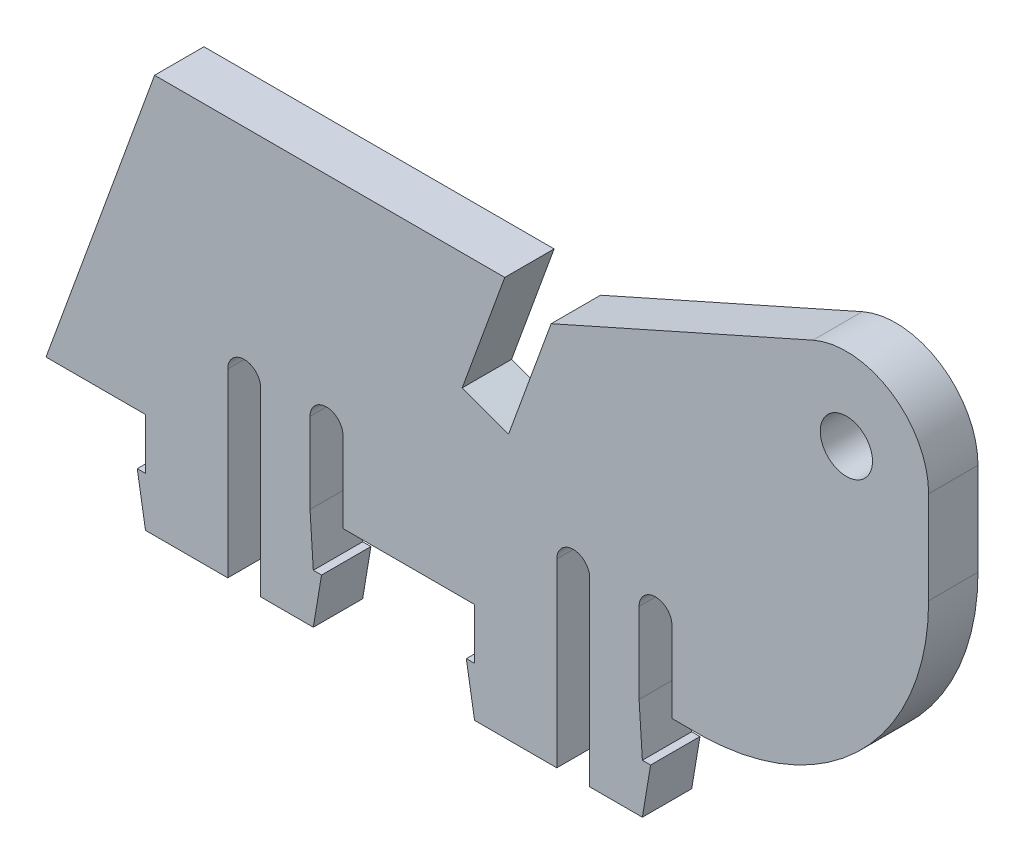
SolidWorks part; units mm, degrees
ref_plane "Front Plane" through (0, 0, 0) normal (0, 0, 1) x (1, 0, 0)
ref_plane "Top Plane" through (0, 0, 0) normal (0, 1, 0) x (1, 0, 0)
ref_plane "Right Plane" through (0, 0, 0) normal (1, 0, 0) x (0, 0, -1)
sketch "Sketch1" plane through (0, 0, 0) normal (0, 0, 1) x (1, 0, 0)
  line L0 (107.5, 145.7123) -> (-107.5, 145.7123) construction
  line L1 (-44.5347, 169.9086) -> (-60.4441, 162.8212)
  line L2 (-60.4441, 162.8212) -> (-63.0315, 155.7123)
  line L3 (-63.0315, 155.7123) -> (-65.8506, 156.7383)
  line L4 (-65.8506, 156.7383) -> (-63.2632, 163.8473)
  line L5 (-84.5467, 163.8473) -> (-91.1473, 145.7123)
  line L11 (-37.5, 165.3413) -> (-37.5, 159.7123)
  line L13 (-42.7842, 211.3413) -> (-67.7631, 142.7123) construction
  line L14 (-67.2603, 211.3413) -> (-92.2392, 142.7123) construction
  line L22 (-91.1473, 145.7123) -> (-51.5, 145.7123)
  line L24 (-63.0315, 155.7123) -> (-65.8506, 156.7383) construction
  line L25 (-47.0687, 208.3413) -> (-70.9557, 142.7123) construction
  line L26 (-63.2632, 163.8473) -> (-84.5467, 163.8473)
  circle A0 centre (-42.5, 165.3413) radius 1.5875
  arc A2 (-44.5347, 169.9086) -> (-37.5, 165.3413) centre (-42.5, 165.3413) cw
  arc A3 (-51.5, 145.7123) -> (-37.5, 159.7123) centre (-51.5, 159.7123) ccw
  dimension "D1" = 3.175
  dimension "D5" = 5
  dimension "D3" = 14
  dimension "D2" = 7.5652
extrude "Boss-Extrude1" add sketch "Sketch1" along normal up to vertex (3 mm away)
sketch "Sketch3" plane through (0, 0, 0) normal (0, 0, -1) x (-1, 0, 0)
  line B0 (54.9, 142.6123) -> (55.1, 145.7123)
  line B1 (53.1, 145.7123) -> (51.1, 145.7123)
  line B2 (65.1, 142.6123) -> (65.1, 145.7123)
  line B3 (65.1, 145.7123) -> (67.1, 145.7123)
  line B4 (58.1, 150.6123) -> (58.1, 139.6123)
  line B5 (65.1, 139.6123) -> (60.1, 139.6123)
  line B6 (60, 150.6123) -> (60, 134.8123) construction
  line B7 (55.1, 145.7123) -> (55.1, 150.6123)
  line B8 (53.1, 150.6123) -> (53.1, 145.7123)
  line B9 (54.9, 142.6123) -> (54.4, 142.6123)
  line B10 (54.4, 142.6123) -> (54.9, 139.6123)
  line B11 (58.1, 139.6123) -> (54.9, 139.6123)
  line B12 (60.1, 139.6123) -> (60.1, 150.6123)
  line B13 (65.1, 142.6123) -> (65.6, 142.6123)
  line B14 (65.6, 142.6123) -> (65.1, 139.6123)
  arc B15 (60.1, 150.6123) -> (58.1, 150.6123) centre (59.1, 150.6123) ccw
  arc B16 (55.1, 150.6123) -> (53.1, 150.6123) centre (54.1, 150.6123) ccw
  line B17 (67.1, 142.7123) -> (51.1, 142.7123) construction
  line B18 (67.1, 142.7123) -> (67.1, 145.7123) construction
  line B19 (59.1, 150.6123) -> (54.1, 150.6123) construction
  line B20 (51.1, 142.7123) -> (51.1, 145.7123) construction
  line B21 (65.1, 145.7123) -> (53.1, 145.7123) construction
  line B22 (67.1, 145.7123) -> (67.1, 152.7123)
  line B23 (67.1, 152.7123) -> (51.1, 152.7123)
  line B24 (51.1, 152.7123) -> (51.1, 145.7123)
  line B25 (74.9, 142.6123) -> (75.1, 145.7123)
  line B26 (73.1, 145.7123) -> (71.1, 145.7123)
  line B27 (85.1, 142.6123) -> (85.1, 145.7123)
  line B28 (85.1, 145.7123) -> (87.1, 145.7123)
  line B29 (78.1, 150.6123) -> (78.1, 139.6123)
  line B30 (85.1, 139.6123) -> (80.1, 139.6123)
  line B31 (80, 150.6123) -> (80, 134.8123) construction
  line B32 (75.1, 145.7123) -> (75.1, 150.6123)
  line B33 (73.1, 150.6123) -> (73.1, 145.7123)
  line B34 (74.9, 142.6123) -> (74.4, 142.6123)
  line B35 (74.4, 142.6123) -> (74.9, 139.6123)
  line B36 (78.1, 139.6123) -> (74.9, 139.6123)
  line B37 (80.1, 139.6123) -> (80.1, 150.6123)
  line B38 (85.1, 142.6123) -> (85.6, 142.6123)
  line B39 (85.6, 142.6123) -> (85.1, 139.6123)
  arc B40 (80.1, 150.6123) -> (78.1, 150.6123) centre (79.1, 150.6123) ccw
  arc B41 (75.1, 150.6123) -> (73.1, 150.6123) centre (74.1, 150.6123) ccw
  line B42 (87.1, 142.7123) -> (71.1, 142.7123) construction
  line B43 (79.1, 150.6123) -> (74.1, 150.6123) construction
  line B44 (71.1, 142.7123) -> (71.1, 145.7123) construction
  line B45 (85.1, 145.7123) -> (73.1, 145.7123) construction
  line B46 (87.1, 145.7123) -> (87.1, 152.7123)
  line B47 (87.1, 152.7123) -> (71.1, 152.7123)
  line B48 (71.1, 152.7123) -> (71.1, 145.7123)
sketch_block_instance "Block1-8"
sketch_block "Block1" parameters "D1"=1, "D2"=8, "D3"=3, "D4"=3.1, "D5"=10, "D6"=0.2, "D7"=0.5, "D8"=3, "D9"=4.3072, "D10"=5, "D11"=0.5
sketch_block_instance "Block1-10"
extrude "tabs" add sketch "Sketch3" against normal up to surface (3 mm away) up to face at (-59.5179, 158.8364, 3)
sketch "Sketch4" plane through (0, 0, 0) normal (0, 0, -1) x (-1, 0, 0)
  line L0 (55.1, 145.7123) -> (55.1, 150.6123) construction
  line L1 (75.1, 145.7123) -> (75.1, 150.6123) construction
  line L2 (55.1, 145.7123) -> (55.1, 150.6123)
  line L3 (75.1, 145.7123) -> (75.1, 150.6123)
  line L4 (53.1, 150.6123) -> (53.1, 145.7123)
  line L5 (53.1, 145.7123) -> (55.1, 145.7123)
  line L7 (58.1, 150.6123) -> (58.1, 145.7123)
  line L8 (58.1, 145.7123) -> (60.1, 145.7123)
  line L9 (60.1, 145.7123) -> (60.1, 150.6123)
  line L10 (73.1, 150.6123) -> (73.1, 145.7123)
  line L11 (73.1, 145.7123) -> (75.1, 145.7123)
  line L12 (78.1, 150.6123) -> (78.1, 145.7123)
  line L13 (78.1, 145.7123) -> (80.1, 145.7123)
  line L14 (80.1, 145.7123) -> (80.1, 150.6123)
  arc A0 (60.1, 150.6123) -> (58.1, 150.6123) centre (59.1, 150.6123) ccw construction
  arc A1 (55.1, 150.6123) -> (53.1, 150.6123) centre (54.1, 150.6123) ccw construction
  arc A2 (75.1, 150.6123) -> (73.1, 150.6123) centre (74.1, 150.6123) ccw construction
  arc A3 (80.1, 150.6123) -> (78.1, 150.6123) centre (79.1, 150.6123) ccw construction
  arc A4 (60.1, 150.6123) -> (58.1, 150.6123) centre (59.1, 150.6123) ccw
  arc A5 (55.1, 150.6123) -> (53.1, 150.6123) centre (54.1, 150.6123) ccw
  arc A6 (75.1, 150.6123) -> (73.1, 150.6123) centre (74.1, 150.6123) ccw
  arc A7 (80.1, 150.6123) -> (78.1, 150.6123) centre (79.1, 150.6123) ccw
extrude "tab relief" cut sketch "Sketch4" against normal up to next
